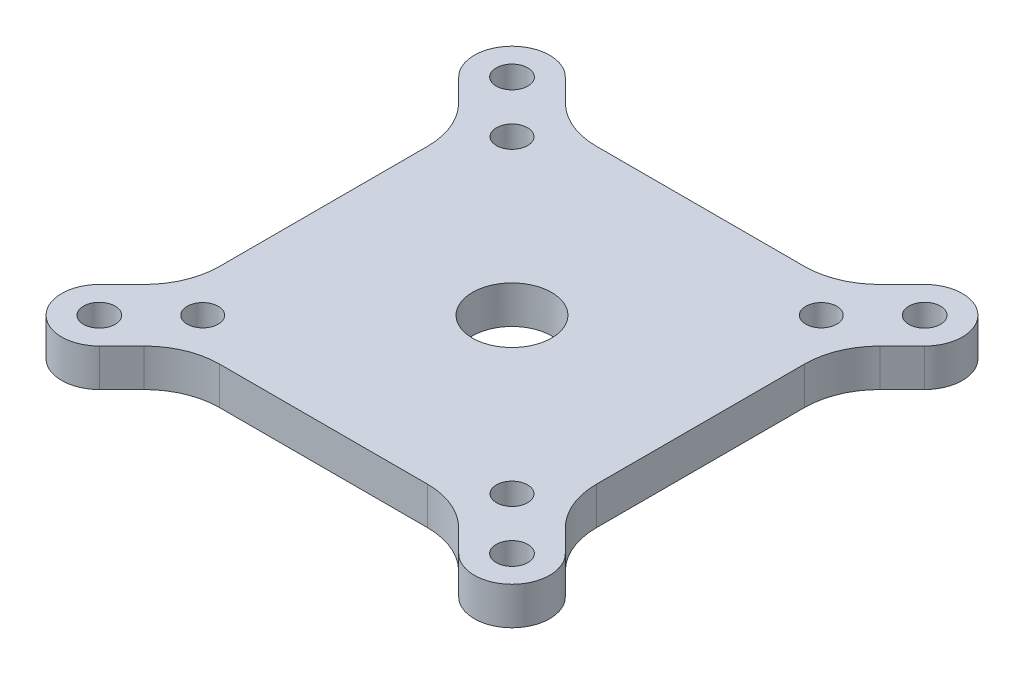
SolidWorks part; units mm, degrees
ref_plane "Front" through (0, 0, 0) normal (0, 0, 1) x (1, 0, 0)
ref_plane "Top" through (0, 0, 0) normal (0, 1, 0) x (1, 0, 0)
ref_plane "Right" through (0, 0, 0) normal (1, 0, 0) x (0, 0, -1)
sketch "Sketch1" plane through (0, 0, 0) normal (0, 1, 0) x (1, 0, 0)
  line L1 (-42.6, -42.6) -> (42.6, -42.6)
  line L2 (-42.6, -42.6) -> (-42.6, 42.6)
  line L3 (-42.6, 42.6) -> (42.6, 42.6)
  line L4 (42.6, -42.6) -> (42.6, 42.6)
  line L5 (-42.6, -42.6) -> (42.6, 42.6) construction
  line L6 (-42.6, 42.6) -> (42.6, -42.6) construction
  point P0 (0, 0)
  dimension "D1" = 85.2
  dimension "D2" = 85.2
extrude "Boss-Extrude1" add sketch "Sketch1" along normal blind 6.35
sketch "Sketch2" plane through (0, 6.35, 0) normal (0, 1, 0) x (1, 0, 0)
  circle A0 centre (0, 0) radius 6.6675
  dimension "D1" = 13.335
extrude "Cut-Extrude1" cut sketch "Sketch2" against normal up to next
sketch "Sketch3" plane through (0, 6.35, 0) normal (0, 1, 0) x (1, 0, 0)
  line L0 (42.6, 0) -> (-42.6, 0) construction
  line L1 (42.6, -42.6) -> (42.6, 42.6) construction
  line L2 (-42.6, 42.6) -> (-42.6, -42.6) construction
  circle A2 centre (26.0427, -26.0427) radius 2.6162 construction
  circle A3 centre (-26.0427, -26.0427) radius 2.6162 construction
  circle A6 centre (26.0427, -26.0427) radius 2.6162
  circle A7 centre (-26.0427, -26.0427) radius 2.6162
  circle A8 centre (26.0427, 26.0427) radius 2.6162
  circle A9 centre (-26.0427, 26.0427) radius 2.6162
extrude "Cut-Extrude2" cut sketch "Sketch3" against normal up to next
sketch "Sketch4" plane through (-42.6, 0, 0) normal (-1, 0, 0) x (0, 0, 1)
  line L4 (-42.6, 0) -> (42.6, 0)
  line L5 (42.6, 0) -> (42.6, 6.35)
  line L6 (42.6, 6.35) -> (-42.6, 6.35)
  line L7 (-42.6, 6.35) -> (-42.6, 0)
  line L8 (-42.6, 0) -> (42.6, 0)
  line L9 (42.6, 0) -> (42.6, 6.35)
  line L10 (42.6, 6.35) -> (-42.6, 6.35)
  line L11 (-42.6, 6.35) -> (-42.6, 0)
  dimension "D1" = 0
sketch "Sketch5" plane through (0, 6.35, 0) normal (0, 1, 0) x (1, 0, 0)
  line L0 (-42.6, -42.6) -> (42.6, -42.6) construction
  line L1 (-42.6, 42.6) -> (-42.6, -42.6) construction
  circle A0 centre (-34.75, -34.75) radius 2.665
  dimension "D1" = 5.33
  dimension "D3" = 7.85
  dimension "D2" = 7.85
extrude "Cut-Extrude3" cut sketch "Sketch5" against normal up to next
pattern_circular "CirPattern1" count 4 over 360 about axis through (0, 0, 0) along (0, 1, 0) of "Cut-Extrude3"
sketch "Sketch6" plane through (0, 6.35, 0) normal (0, 1, 0) x (1, 0, 0)
  line L0 (39.2401, -30.2599) -> (31.75, -22.7697)
  line L5 (-31.75, -31.75) -> (31.75, -31.75)
  line L6 (-31.75, -31.75) -> (-31.75, 31.75)
  line L7 (-31.75, 31.75) -> (31.75, 31.75)
  line L8 (31.75, -31.75) -> (31.75, 31.75)
  line L9 (-31.75, -31.75) -> (31.75, 31.75) construction
  line L10 (-31.75, 31.75) -> (31.75, -31.75) construction
  line L11 (30.2599, -39.2401) -> (22.7697, -31.75)
  line L12 (-39.2401, -30.2599) -> (-31.75, -22.7697)
  line L13 (-30.2599, -39.2401) -> (-22.7697, -31.75)
  line L14 (-30.2599, 39.2401) -> (-22.7697, 31.75)
  line L15 (-39.2401, 30.2599) -> (-31.75, 22.7697)
  line L16 (39.2401, 30.2599) -> (31.75, 22.7697)
  line L17 (30.2599, 39.2401) -> (22.7697, 31.75)
  line L22 (42.6, -42.6) -> (42.6, 42.6)
  line L23 (42.6, 42.6) -> (-42.6, 42.6)
  line L24 (-42.6, 42.6) -> (-42.6, -42.6)
  line L25 (-42.6, -42.6) -> (42.6, -42.6)
  line L26 (42.6, -42.6) -> (42.6, 42.6)
  line L27 (42.6, 42.6) -> (-42.6, 42.6)
  line L28 (-42.6, 42.6) -> (-42.6, -42.6)
  line L29 (-42.6, -42.6) -> (42.6, -42.6)
  circle A0 centre (34.75, -34.75) radius 6.35
  circle A1 centre (-34.75, -34.75) radius 6.35
  circle A2 centre (-34.75, 34.75) radius 6.35
  circle A3 centre (34.75, 34.75) radius 6.35
  point P0 (0, 0)
  point P34 (0, 0)
  line M22 (42.6, -42.6) -> (42.6, 42.6)
  line M23 (42.6, 42.6) -> (-42.6, 42.6)
  line M24 (-42.6, 42.6) -> (-42.6, -42.6)
  line M25 (-42.6, -42.6) -> (42.6, -42.6)
  dimension "D2" = 12.7
  dimension "D1" = 63.5
  dimension "D4" = 0
  dimension "D3" = 4
extrude "Cut-Extrude4" cut sketch "Sketch6" against normal up to next contours A3 L16 L8 L0 A0 L11 L5 L13 A1 L12 L6 L15 A2 L14 L7 L17 M25 M22 M23 M24
fillet "Fillet1" radius 12.7 8 edges at (-31.75, 3.175, 22.7697) (-31.75, 3.175, -22.7697) (-22.7697, 3.175, -31.75) (22.7697, 3.175, -31.75) (31.75, 3.175, -22.7697) (31.75, 3.175, 22.7697) (22.7697, 3.175, 31.75) (-22.7697, 3.175, 31.75)
